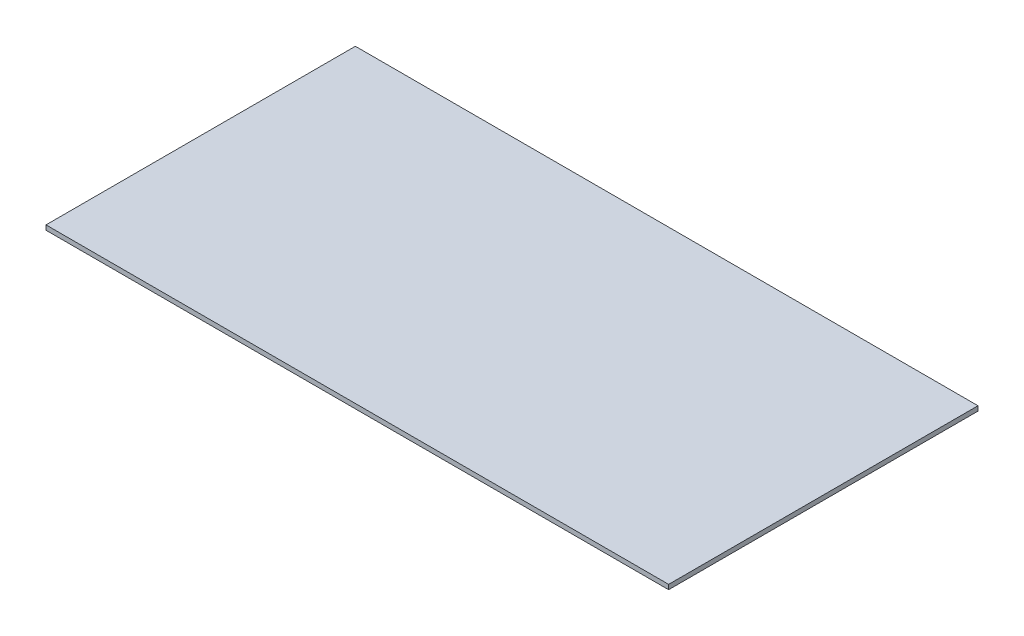
SolidWorks part; units mm, degrees
material "Тик"
ref_plane "Спереди" through (0, 0, 0) normal (0, 0, 1) x (1, 0, 0)
ref_plane "Сверху" through (0, 0, 0) normal (0, 1, 0) x (1, 0, 0)
ref_plane "Справа" through (0, 0, 0) normal (1, 0, 0) x (0, 0, -1)
sketch "Эскиз1" plane through (0, 0, 0) normal (0, 1, 0) x (1, 0, 0)
  line L1 (-802.046, 363.2864) -> (797.954, 363.2864)
  line L2 (-802.046, 363.2864) -> (-802.046, -431.7136)
  line L3 (-802.046, -431.7136) -> (797.954, -431.7136)
  line L4 (797.954, 363.2864) -> (797.954, -431.7136)
  dimension "D1" = 1600
  dimension "D2" = 795
extrude "Бобышка-Вытянуть1" add sketch "Эскиз1" along normal blind 12
